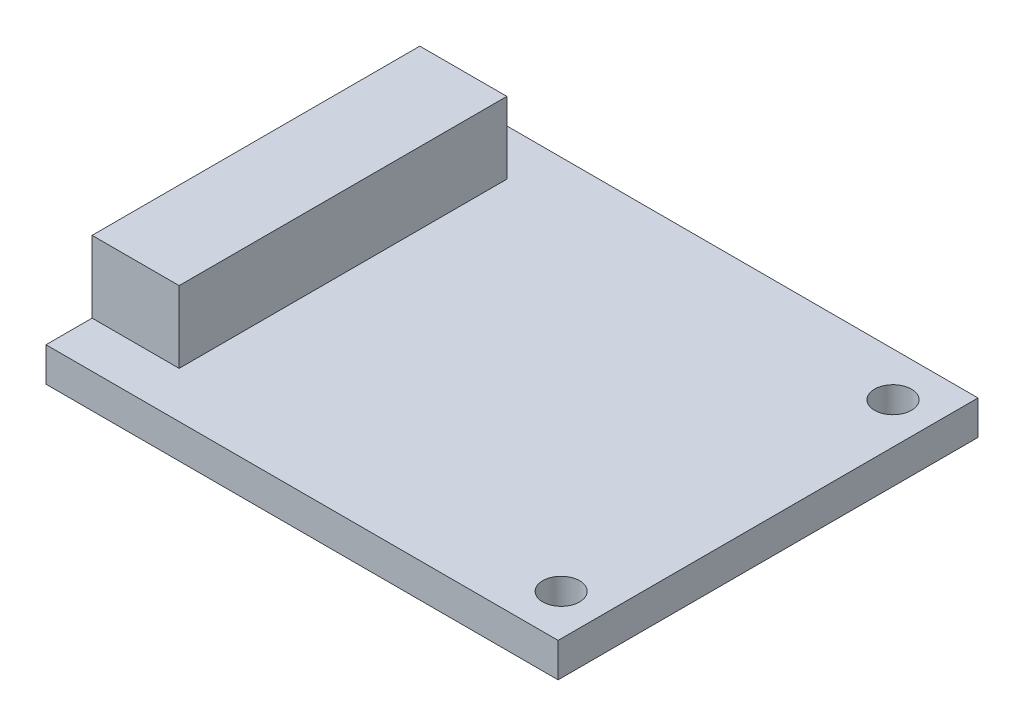
SolidWorks part; units mm, degrees
ref_plane "Front Plane" through (0, 0, 0) normal (0, 0, 1) x (1, 0, 0)
ref_plane "Top Plane" through (0, 0, 0) normal (0, 1, 0) x (1, 0, 0)
ref_plane "Right Plane" through (0, 0, 0) normal (1, 0, 0) x (0, 0, -1)
sketch "Sketch1" plane through (0, 0, 0) normal (0, 1, 0) x (1, 0, 0)
  line L1 (0, 0) -> (25, 0)
  line L2 (0, 0) -> (0, 20.5)
  line L3 (0, 20.5) -> (25, 20.5)
  line L4 (25, 0) -> (25, 20.5)
  dimension "D1" = 25
  dimension "D2" = 20.5
extrude "Boss-Extrude1" add sketch "Sketch1" along normal blind 1.67
hole_wizard "M1.6 Clearance Hole1" positions "Sketch2" profile "Sketch3" hole size "M1.6" standard "ANSI Metric" end condition through all
sketch "Sketch2" plane through (0, 1.67, 0) normal (0, 1, 0) x (1, 0, 0)
  line L0 (23, 18.35) -> (23, 2.15) construction
  line L2 (25, 10.25) -> (23, 10.25) construction
  line L3 (25, 0) -> (25, 20.5) construction
  point P0 (23, 18.35)
  point P2 (23, 2.15)
  dimension "D1" = 16.2
  dimension "D2" = 2
sketch "Sketch3" plane through (23, 1.67, -18.35) normal (1, 0, 0) x (0, 0, 1)
  line L0 (0, 0) -> (0, 1.67)
  line L1 (0, 1.67) -> (0.9, 1.67)
  line L2 (0.9, 1.67) -> (0.9, 0)
  line L5 (0.9, 0) -> (0, 0)
  line L11 (0, -6.35) -> (0, 107.95) construction
  dimension "Thru Hole Dia." = 1.8
  dimension "Thru Hole Depth" = 1.67
sketch "Sketch4" plane through (0, 1.67, 0) normal (0, 1, 0) x (1, 0, 0)
  line L0 (0, 20.5) -> (0, 0) construction
  line L1 (0, 2.25) -> (4.25, 2.25)
  line L2 (0, 2.25) -> (0, 18.25)
  line L3 (0, 18.25) -> (4.25, 18.25)
  line L4 (4.25, 2.25) -> (4.25, 18.25)
  line L5 (4.25, 10.25) -> (25, 10.25) construction
  line L6 (25, 0) -> (25, 20.5) construction
  dimension "D1" = 16
  dimension "D2" = 4.25
extrude "Boss-Extrude2" add sketch "Sketch4" along normal blind 3.5
